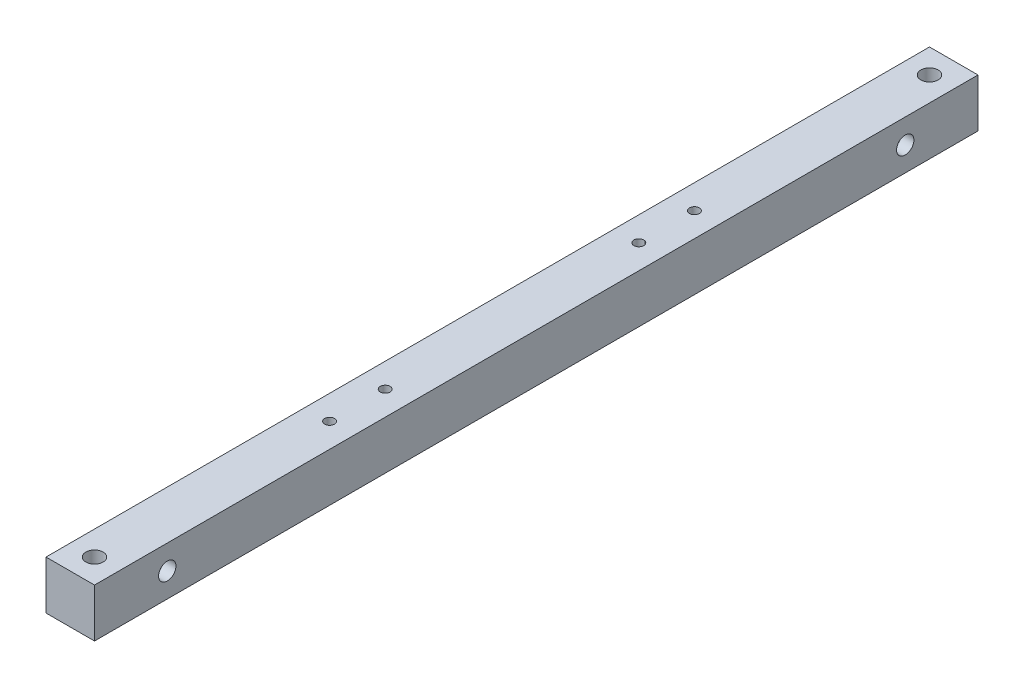
SolidWorks part; units mm, degrees
ref_plane "Ön Düzlem" through (0, 0, 0) normal (0, 0, 1) x (1, 0, 0)
ref_plane "Üst Düzlem" through (0, 0, 0) normal (0, 1, 0) x (1, 0, 0)
ref_plane "Sağ Düzlem" through (0, 0, 0) normal (1, 0, 0) x (0, 0, -1)
sketch "Çizim1" plane through (0, 0, 0) normal (0, 0, 1) x (1, 0, 0)
  line L1 (-14, -14) -> (14, -14)
  line L2 (-14, -14) -> (-14, 14)
  line L3 (-14, 14) -> (14, 14)
  line L4 (14, -14) -> (14, 14)
  line L5 (-14, -14) -> (14, 14) construction
  line L6 (-14, 14) -> (14, -14) construction
  point P0 (0, 0)
  dimension "D1" = 28
  dimension "D2" = 28
extrude "Yükseklik-Ekstrüzyon1" add sketch "Çizim1" along normal mid plane 510
sketch "Çizim2" plane through (14, 0, 0) normal (1, 0, 0) x (0, 0, -1)
  line L2 (255, -14) -> (255, 14) construction
  line L3 (-255, -14) -> (-255, 14) construction
  line L5 (-255, 14) -> (255, 14) construction
  circle A0 centre (-213, 0) radius 5
  circle A1 centre (213, 0) radius 5
  dimension "D3" = 14
  dimension "D5" = 10
  dimension "D1" = 42
  dimension "D2" = 42
  dimension "D4" = 14
extrude "Kes-Ekstrüzyon1" cut sketch "Çizim2" against normal blind 7
sketch "Çizim3" plane through (14, 0, 0) normal (1, 0, 0) x (0, 0, -1)
  circle A0 centre (-213, 0) radius 3
  circle A1 centre (213, 0) radius 3
  dimension "D1" = 6
extrude "Kes-Ekstrüzyon2" cut sketch "Çizim3" along direction (1, 0, 0) on the side against the normal through all and the other way through all
sketch "Çizim4" plane through (0, -14, 0) normal (0, -1, 0) x (1, 0, 0)
  line L0 (-14, -255) -> (14, -255) construction
  line L1 (-14, 255) -> (14, 255) construction
  circle A0 centre (0, -241) radius 3
  circle A1 centre (0, 241) radius 3
  dimension "D3" = 6
  dimension "D1" = 14
  dimension "D2" = 14
extrude "Kes-Ekstrüzyon3" cut sketch "Çizim4" against normal up to next
sketch "Çizim6" plane through (0, 14, 0) normal (0, 1, 0) x (1, 0, 0)
  circle A0 centre (0, -241) radius 5
  circle A1 centre (0, 241) radius 5
  dimension "D1" = 10
extrude "Kes-Ekstrüzyon5" cut sketch "Çizim6" against normal blind 7
sketch "Çizim7" plane through (0, 14, 0) normal (0, 1, 0) x (1, 0, 0)
  line L0 (-14, -255) -> (-14, 255) construction
  line L1 (-14, -255) -> (-14, 255) construction
  line L2 (-14, 0) -> (14, 0) construction
  line L3 (14, -255) -> (14, 255) construction
  line L4 (0, -105.3) -> (0, -73.2) construction
  circle A0 centre (0, -105.3) radius 2.85
  circle A1 centre (0, -73.2) radius 2.85
  circle A2 centre (0, 73.2) radius 2.85
  circle A3 centre (0, 105.3) radius 2.85
  point P10 (0, -89.25)
  point P11 (0, 0)
  dimension "D1" = 32.1
  dimension "D2" = 5.7
  dimension "D3" = 89.25
extrude "Kes-Ekstrüzyon6" cut sketch "Çizim7" against normal through all
